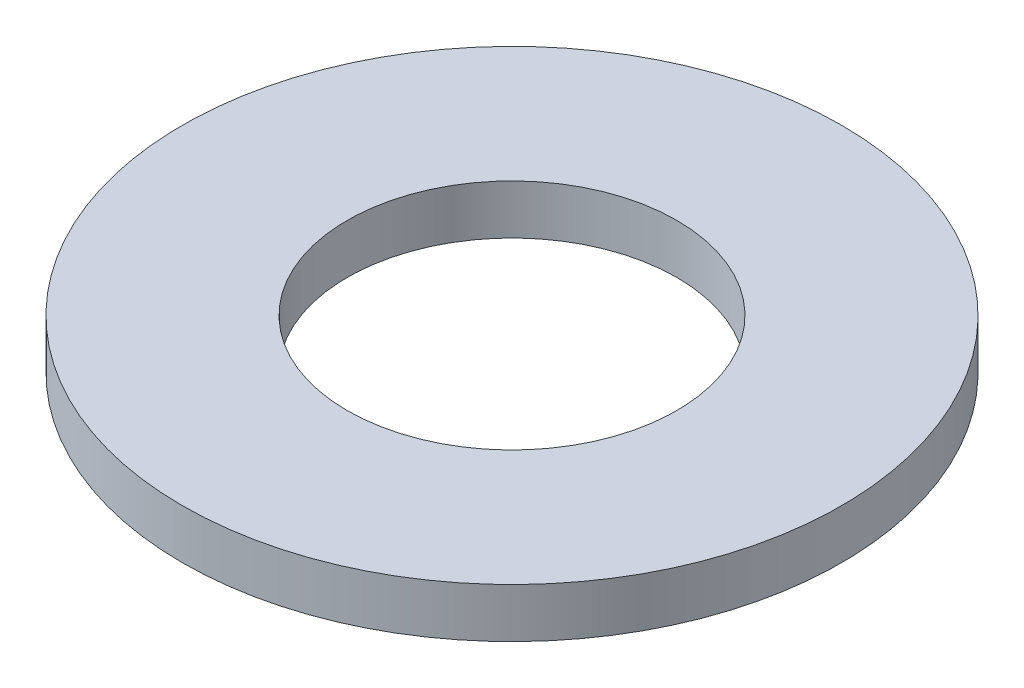
SolidWorks part; units mm, degrees
material "Cast Stainless Steel"
ref_plane "Front Plane" through (0, 0, 0) normal (0, 0, 1) x (1, 0, 0)
ref_plane "Top Plane" through (0, 0, 0) normal (0, 1, 0) x (1, 0, 0)
ref_plane "Right Plane" through (0, 0, 0) normal (1, 0, 0) x (0, 0, -1)
sketch "Sketch1" plane through (0, 0, 0) normal (0, 1, 0) x (1, 0, 0)
  circle A0 centre (0, 0) radius 1
  circle A1 centre (0, 0) radius 2
extrude "Boss-Extrude1" add sketch "Sketch1" along normal blind 0.3
